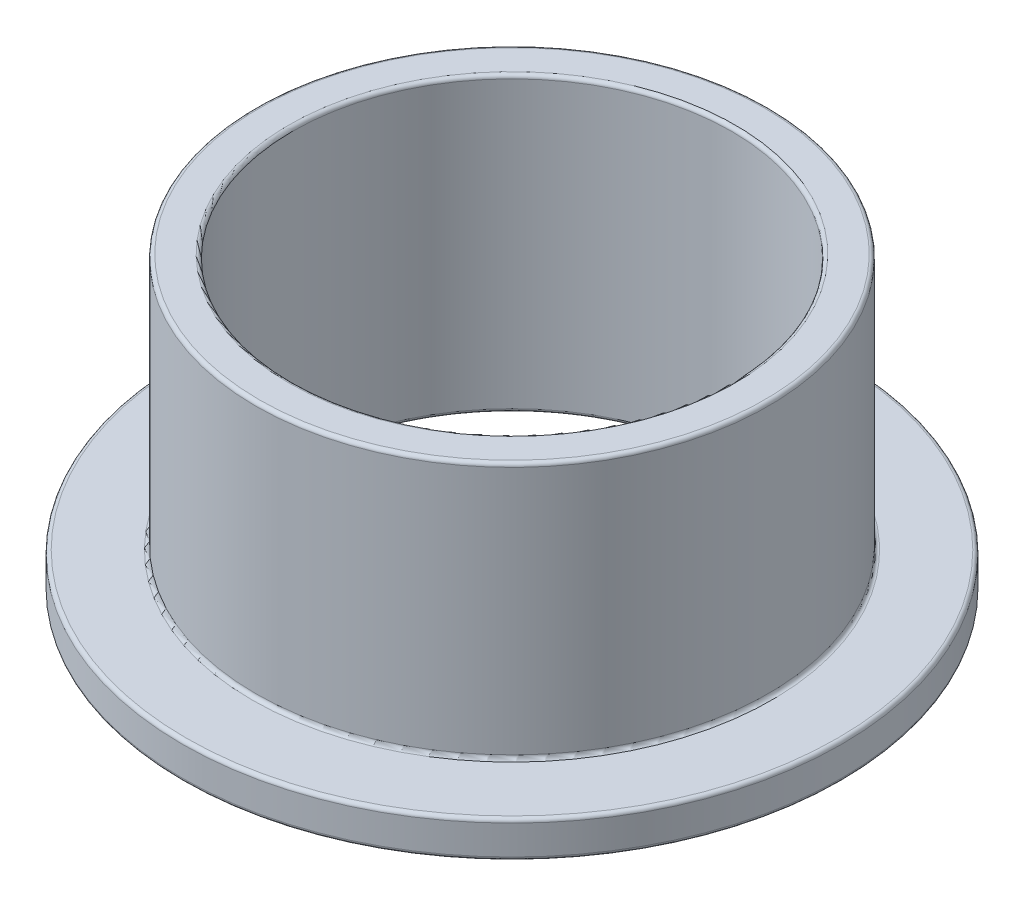
SolidWorks part; units mm, degrees
ref_plane "Front" through (0, 0, 0) normal (0, 0, 1) x (1, 0, 0)
ref_plane "Top" through (0, 0, 0) normal (0, 1, 0) x (1, 0, 0)
ref_plane "Right" through (0, 0, 0) normal (1, 0, 0) x (0, 0, -1)
sketch "Sketch1" plane through (0, 0, 0) normal (0, 1, 0) x (1, 0, 0)
  circle A0 centre (0, 0) radius 9.525
  circle A1 centre (0, 0) radius 11.1125
  circle A2 centre (0, 0) radius 14.2875
  dimension "ID" = 19.05
  dimension "OD" = 22.225
  dimension "FlangeOD" = 28.575
sketch "Sketch2" plane through (0, 0, 0) normal (1, 0, 0) x (0, 0, -1)
  line L0 (14.2875, 0) -> (14.2875, 1.5875) construction
  line L1 (-11.1125, 0) -> (-11.1125, 12.7) construction
  line L2 (11.1125, 12.7) -> (-11.1125, 12.7) construction
  line L8 (0, 0) -> (0, 12.7) construction
  point P5 (-14.2875, 0)
  point P39 (0, 12.7)
  dimension "Flange Thickness" = 1.5875
  dimension "Length" = 12.7
  dimension "D1" = 22.225
sketch "Sketch3" plane through (0, 0, 0) normal (0, 1, 0) x (1, 0, 0)
  circle A0 centre (0, 0) radius 9.525 construction
  circle A1 centre (0, 0) radius 11.1125 construction
  circle A2 centre (0, 0) radius 9.525
  circle A3 centre (0, 0) radius 11.1125
extrude "Boss-Extrude1" add sketch "Sketch3" along normal up to vertex (12.7 mm away) up to point (0, 12.7, 11.1125)
sketch "Sketch4" plane through (0, 0, 0) normal (0, 1, 0) x (1, 0, 0)
  circle A0 centre (0, 0) radius 14.2875 construction
  circle A1 centre (0, 0) radius 11.1125 construction
  circle A2 centre (0, 0) radius 14.2875
  circle A3 centre (0, 0) radius 11.1125
extrude "Boss-Extrude2" add sketch "Sketch4" along normal up to vertex (1.5875 mm away) up to point (0, 1.5875, -14.2875)
fillet "Fillet1" radius 0.1588 6 edges at (0, 0, 9.525) (0, 0, 14.2875) (0, 1.5875, 11.1125) (0, 1.5875, 14.2875) (0, 12.7, 9.525) (0, 12.7, 11.1125)
equation "\"D1@Fillet1\"=(\"OD@Sketch1\"-\"ID@Sketch1\")*.05"
equation "\"D1@Sketch2\"=\"OD@Sketch1\""
